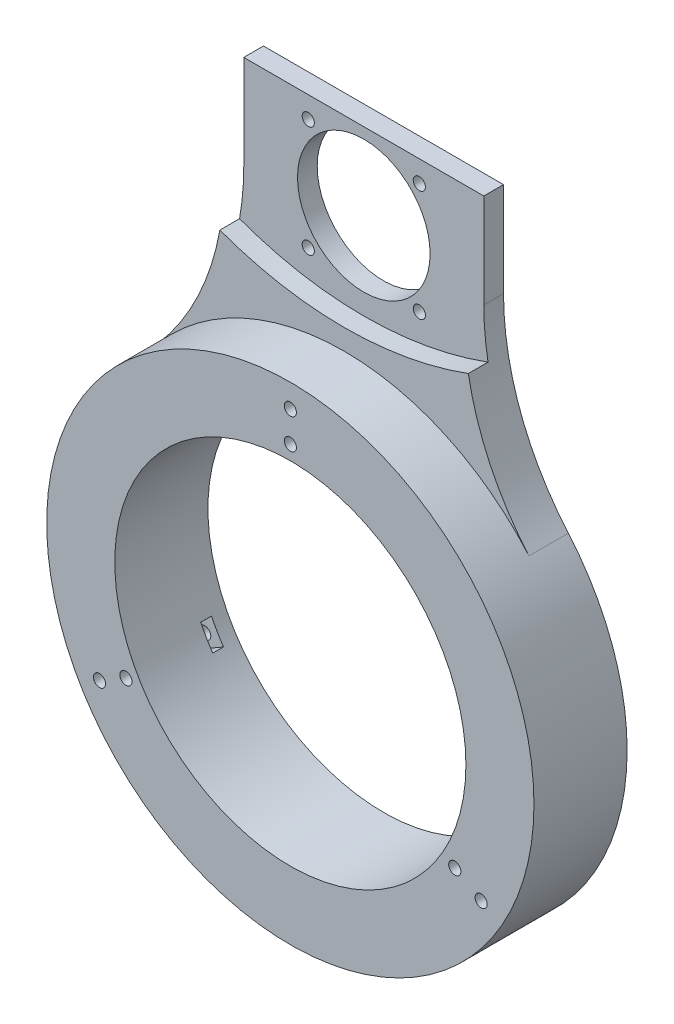
SolidWorks part; units mm, degrees
ref_plane "Front Plane" through (0, 0, 0) normal (0, 0, 1) x (1, 0, 0)
ref_plane "Top Plane" through (0, 0, 0) normal (0, 1, 0) x (1, 0, 0)
ref_plane "Right Plane" through (0, 0, 0) normal (1, 0, 0) x (0, 0, -1)
sketch "Sketch1" plane through (0, 0, 0) normal (0, 0, 1) x (1, 0, 0)
  circle A0 centre (0, 0) radius 68
  circle A1 centre (0, 0) radius 49
  dimension "D1" = 136
  dimension "D2" = 98
extrude "Boss-Extrude1" add sketch "Sketch1" along normal blind 15 and the other way blind 11
sketch "Sketch2" plane through (0, 0, -11) normal (0, 0, -1) x (-1, 0, 0)
  line L0 (-76.2552, 0) -> (83.6012, 0) construction
  line L1 (-21.5, 119.5) -> (21.5, 119.5)
  line L2 (-21.5, 119.5) -> (-21.5, 76.5)
  line L3 (-21.5, 76.5) -> (21.5, 76.5)
  line L4 (21.5, 119.5) -> (21.5, 76.5)
  line L5 (-21.5, 119.5) -> (21.5, 76.5) construction
  line L6 (-21.5, 76.5) -> (21.5, 119.5) construction
  line L7 (-33.5, 119.5) -> (33.5, 119.5)
  line L8 (-33.5, 119.5) -> (-33.5, 66.5)
  line L9 (-33.5, 66.5) -> (33.5, 66.5)
  line L10 (33.5, 119.5) -> (33.5, 66.5)
  line L11 (-33.5, 119.5) -> (33.5, 66.5) construction
  line L12 (-33.5, 66.5) -> (33.5, 119.5) construction
  line L13 (-59.5091, 98) -> (49.588, 98) construction
  line L14 (0, 0) -> (-73.46, 73.46) construction
  line L15 (0, 0) -> (0, 98) construction
  line L16 (0, 0) -> (73.46, 73.46) construction
  line L17 (-51.5944, 44.2947) -> (51.5944, 44.2947)
  circle A0 centre (-33.5, 98) radius 2.5982 construction
  circle A1 centre (-48.0833, 48.0833) radius 10.7942 construction
  circle A2 centre (0, 0) radius 68 construction
  circle A3 centre (48.0833, 48.0833) radius 10.7942 construction
  circle A4 centre (33.5, 98) radius 2.5982 construction
  arc A5 (-51.5944, 44.2947) -> (-33.5, 93.1491) centre (-108.5, 93.1491) ccw
  circle A6 centre (-0.7791, 0.7791) radius 34.0704
  circle A7 centre (0, 0) radius 68 construction
  arc A8 (51.5944, 44.2947) -> (33.5, 93.1491) centre (108.5, 93.1491) cw
  circle A9 centre (0, 98) radius 18.5
  point P0 (0, 98)
  point P5 (0, 93)
  circle M5 centre (0, 0) radius 49
  circle M6 centre (0, 0) radius 68
  dimension "D8" = 136
  dimension "D9" = 75
  dimension "D5" = 37
  dimension "D1" = 43
  dimension "D2" = 43
  dimension "D3" = 76.5
  dimension "D4" = 12
  dimension "D6" = 10
  dimension "D7" = 45
extrude "Boss-Extrude2" add sketch "Sketch2" against normal blind 11 contours A5 L9 L8 M6 | L17 L9 M6 M5 | A8 L10 L9 M6 | L9 M6 | L10 L7 L4 L3 L2 L8 L9 M6 | L4 L1 L2 L3 A9
sketch "Sketch3" plane through (0, 0, -11) normal (0, 0, -1) x (-1, 0, 0)
  line L1 (-15.5, 82.5) -> (15.5, 82.5)
  line L2 (-15.5, 82.5) -> (-15.5, 113.5)
  line L3 (-15.5, 113.5) -> (15.5, 113.5)
  line L4 (15.5, 82.5) -> (15.5, 113.5) construction
  line L5 (-15.5, 82.5) -> (15.5, 113.5) construction
  line L6 (-15.5, 113.5) -> (15.5, 82.5) construction
  circle A0 centre (-15.5, 113.5) radius 1.7
  circle A1 centre (15.5, 113.5) radius 1.7
  circle A2 centre (15.5, 82.5) radius 1.7
  circle A3 centre (-15.5, 82.5) radius 1.7
  point P0 (0, 98)
  point P16 (0, 98)
  dimension "D3" = 3.4
  dimension "D1" = 31
  dimension "D2" = 31
  dimension "D4" = 4
extrude "Cut-Extrude1" cut sketch "Sketch3" against normal through all contours A0 | A1 | A2 | A3
sketch "Sketch4" plane through (0, 0, 0) normal (0, 0, 1) x (1, 0, 0)
  line L1 (-33.5, 116.5) -> (33.5, 116.5) construction
  line L2 (-33.5, 116.5) -> (-33.5, 79.5)
  line L3 (-33.5, 79.5) -> (33.5, 79.5)
  line L4 (33.5, 116.5) -> (33.5, 79.5)
  line L5 (-33.5, 116.5) -> (33.5, 79.5) construction
  line L6 (-33.5, 79.5) -> (33.5, 116.5) construction
  line L8 (-33.5, 119.5) -> (33.5, 119.5)
  line L9 (-33.5, 119.5) -> (-33.5, 98)
  line L10 (-33.5, 98) -> (33.5, 98) construction
  line L11 (33.5, 119.5) -> (33.5, 98)
  circle A0 centre (0, 98) radius 18.5
  circle A2 centre (0, 173.7218) radius 100
  circle A3 centre (0, 0) radius 68
  circle M9 centre (15.5, 82.5) radius 1.7
  circle M10 centre (-15.5, 82.5) radius 1.7
  circle M11 centre (-15.5, 113.5) radius 1.7
  circle M12 centre (15.5, 113.5) radius 1.7
  arc M14 (51.5944, 44.2947) -> (33.5, 93.1491) centre (108.5, 93.1491) cw
  line M15 (33.5, 93.1491) -> (33.5, 119.5)
  line M16 (33.5, 119.5) -> (-33.5, 119.5)
  line M17 (-33.5, 119.5) -> (-33.5, 93.1491)
  arc M18 (-33.5, 93.1491) -> (-51.5944, 44.2947) centre (-108.5, 93.1491) cw
  circle M19 centre (0, 98) radius 18.5
  dimension "D3" = 200
  dimension "D4" = 136
  dimension "D1" = 37
  dimension "D2" = 67
extrude "Cut-Extrude2" cut sketch "Sketch4" against normal blind 5.5 contours L4 L2 L3 M15 M16 M17 M19 M10 M12 M11 M9 | L3 A2 | A2 L2 M18 | L4 A2 M14
sketch "Sketch5" plane through (0, 0, -11) normal (0, 0, -1) x (-1, 0, 0)
  circle A0 centre (0, 61.5) radius 1.7
  circle A1 centre (0, 0) radius 61.5 construction
  circle A2 centre (53.2606, -30.75) radius 1.7
  circle A3 centre (-53.2606, -30.75) radius 1.7
  circle A4 centre (0, 0) radius 53 construction
  circle A5 centre (0, 53) radius 1.7
  circle A6 centre (0, 0) radius 53 construction
  circle A7 centre (45.8993, -26.5) radius 1.7
  circle A8 centre (0, 0) radius 53 construction
  circle A9 centre (-45.8993, -26.5) radius 1.7
  point P12 (0, 0)
  point P21 (0, 0)
  dimension "D1" = 3.4
  dimension "D2" = 123
  dimension "D4" = 106
  dimension "D5" = 3.4
  dimension "D3" = 3
  dimension "D6" = 3
extrude "Cut-Extrude3" cut sketch "Sketch5" against normal through all
sketch "Sketch6" plane through (0, 0, -11) normal (0, 0, -1) x (-1, 0, 0)
  circle A0 centre (0, 61.5) radius 2.95
  dimension "D1" = 5.9
extrude "Cut-Extrude4" cut sketch "Sketch6" against normal blind 3
pattern_circular "CirPattern1" count 3 over 360 about axis through (0, 0, 0) along (0, 0, 1) of "Cut-Extrude4"
ref_plane "Plane1" through (0, 0, -7) normal (0, 0, -1) x (-1, 0, 0)
sketch "Sketch7" plane through (0, 0, -7) normal (0, 0, -1) x (-1, 0, 0)
  line L0 (-3.35, 53) -> (3.35, 53) construction
  line L1 (-1.675, 55.9012) -> (1.675, 50.0988) construction
  line L2 (-1.675, 50.0988) -> (1.675, 55.9012) construction
  line L3 (-1.675, 50.0988) -> (-3.35, 53)
  line L4 (-3.35, 53) -> (-1.675, 55.9012)
  line L5 (-1.675, 55.9012) -> (1.675, 55.9012)
  line L6 (1.675, 55.9012) -> (3.35, 53)
  line L7 (3.35, 53) -> (1.675, 50.0988)
  line L8 (1.675, 50.0988) -> (-1.675, 50.0988)
  line L9 (-3.35, 53) -> (-3.35, 44)
  line L10 (-3.35, 44) -> (3.35, 44)
  line L11 (3.35, 44) -> (3.35, 53)
  circle A0 centre (0, 53) radius 3.35 construction
  dimension "D1" = 6.7
  dimension "D2" = 60
  dimension "D3" = 60
  dimension "D4" = 9
extrude "Cut-Extrude5" cut sketch "Sketch7" against normal blind 3 contours L10 L11 L7 L8 L3 L9 | L8 L7 L6 L5 L4 L3
pattern_circular "CirPattern2" count 3 over 360 about axis through (0, 0, 0) along (0, 0, 1) of "Cut-Extrude5"
equation "\"D3@Sketch2\"=68+(60/2)-(43/2)"
